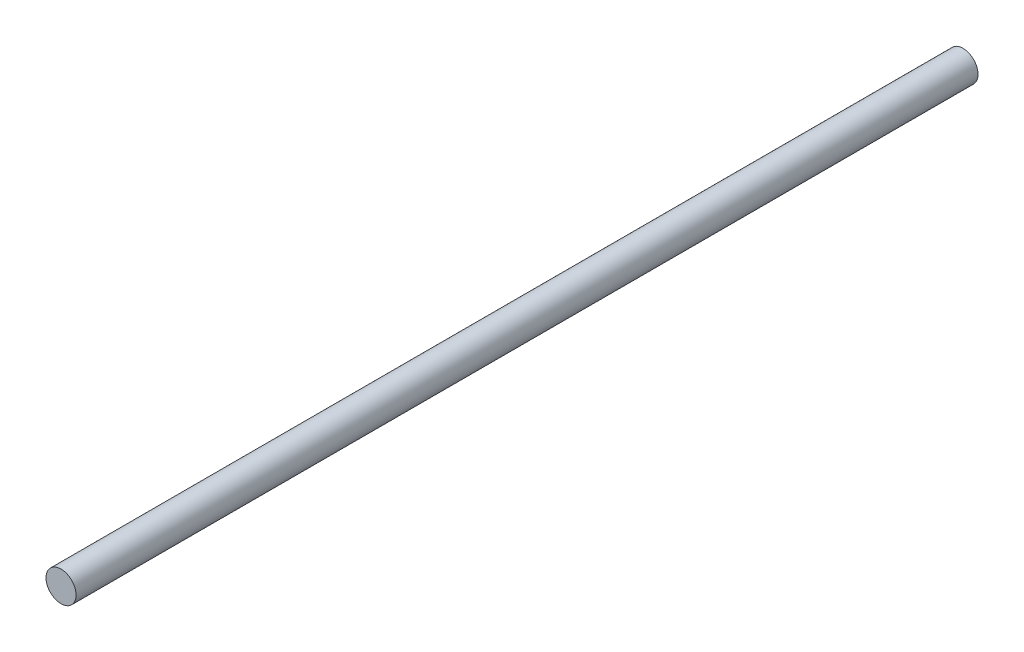
SolidWorks part; units mm, degrees
material "Plain Carbon Steel"
ref_plane "Front Plane" through (0, 0, 0) normal (0, 0, 1) x (1, 0, 0)
ref_plane "Top Plane" through (0, 0, 0) normal (0, 1, 0) x (1, 0, 0)
ref_plane "Right Plane" through (0, 0, 0) normal (1, 0, 0) x (0, 0, -1)
sketch "Sketch1" plane through (0, 0, 0) normal (0, 0, 1) x (1, 0, 0)
  circle A0 centre (0, 0) radius 3
  dimension "D1" = 6
extrude "Boss-Extrude1" add sketch "Sketch1" along normal mid plane 180
